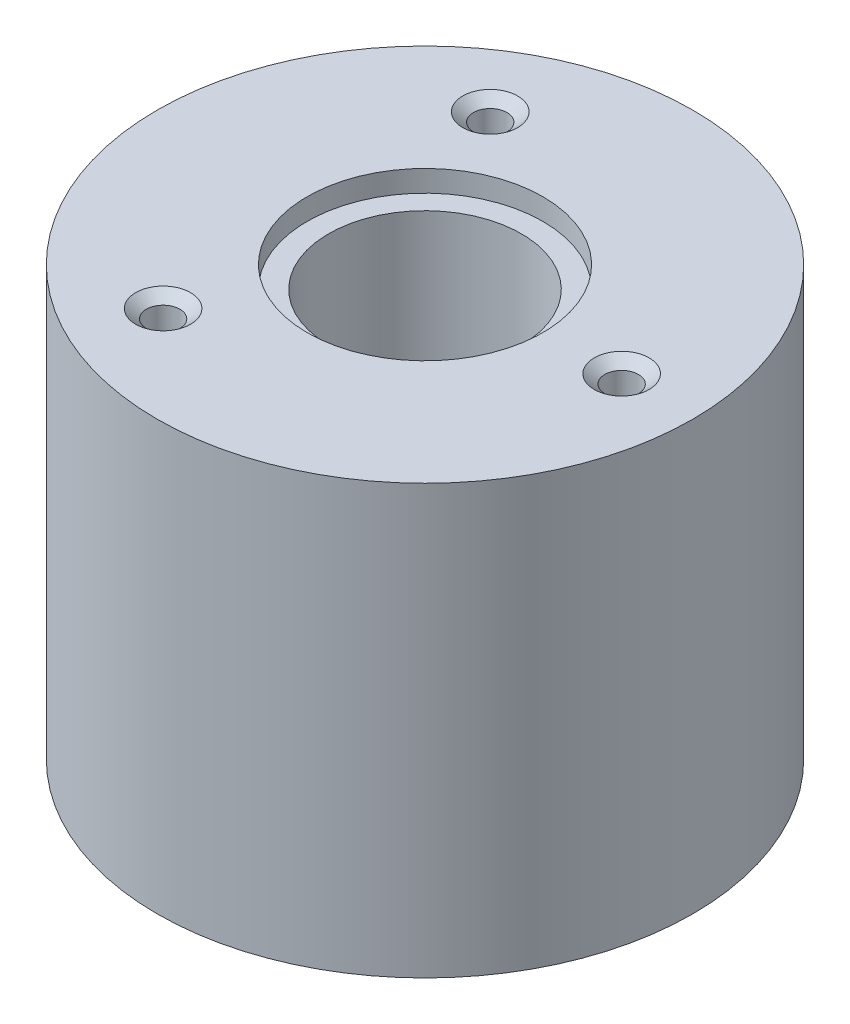
SolidWorks part; units mm, degrees
material "Copper"
ref_plane "Front Plane" through (0, 0, 0) normal (0, 0, 1) x (1, 0, 0)
ref_plane "Top Plane" through (0, 0, 0) normal (0, 1, 0) x (1, 0, 0)
ref_plane "Right Plane" through (0, 0, 0) normal (1, 0, 0) x (0, 0, -1)
sketch "Sketch1" plane through (0, 0, 0) normal (0, 1, 0) x (1, 0, 0)
  circle A0 centre (0, 0) radius 15.875
  dimension "D1" = 31.75
extrude "Boss-Extrude1" add sketch "Sketch1" along normal blind 25.4
sketch "Sketch2" plane through (0, 25.4, 0) normal (0, 1, 0) x (1, 0, 0)
  circle A0 centre (0, 0) radius 5.715
  dimension "D1" = 11.43
extrude "Cut-Extrude1" cut sketch "Sketch2" against normal through all contours A0
sketch "Sketch3" plane through (0, 25.4, 0) normal (0, 1, 0) x (1, 0, 0)
  circle A0 centre (0, 0) radius 6.985
  dimension "D1" = 13.97
extrude "Cut-Extrude2" cut sketch "Sketch3" against normal blind 1.27
hole_wizard "1/4 (0.25) Diameter Hole2" positions "Sketch9" profile "Sketch10" hole size "1/4" standard "ANSI Inch"
sketch "Sketch9" plane through (0, 0, 0) normal (0, -1, 0) x (-1, 0, 0)
  point P0 (-8.9174, -6.4367)
sketch "Sketch10" plane through (8.9174, 0, 6.4367) normal (1, 0, 0) x (0, 0, -1)
  line L0 (0, 0) -> (0, 20.9577)
  line L1 (0, 20.9577) -> (3.175, 19.05)
  line L2 (3.175, 19.05) -> (3.175, 0)
  line L5 (3.175, 0) -> (0, 0)
  line L10 (0, 20.9577) -> (-3.175, 19.05) construction
  line L11 (0, -6.35) -> (0, 107.95) construction
  dimension "Hole Dia." = 6.35
  dimension "Hole Depth" = 19.05
  dimension "Drill Angle" = 118
pattern_circular "CirPattern3" count 2 every 180 about axis through (0, 0, 0) along (0, 1, 0) of "1/4 (0.25) Diameter Hole2"
sketch "Sketch11" plane through (0, 25.4, 0) normal (0, 1, 0) x (1, 0, 0)
  line L0 (0, 0) -> (-5.9142, 9.781)
  line L1 (0, 0) -> (9.5462, 5.6883)
  dimension "D1" = 11.43
  dimension "D2" = 11.1125
hole_wizard "5/64 (0.07813) Diameter Hole1" positions "Sketch12" profile "Sketch13" hole size "5/64" standard "ANSI Inch"
sketch "Sketch12" plane through (0, 25.4, 0) normal (0, 1, 0) x (1, 0, 0)
  point P0 (-5.9142, 9.781)
sketch "Sketch13" plane through (-5.9142, 25.4, -9.781) normal (1, 0, 0) x (0, 0, 1)
  line L0 (0, 0) -> (0, 10.7562)
  line L1 (0, 10.7562) -> (0.9923, 10.16)
  line L2 (0.9923, 10.16) -> (0.9923, 0.5328)
  line L3 (0.9923, 0.5328) -> (1.6273, 0)
  line L5 (1.6273, 0) -> (0, 0)
  line L6 (-0.9923, 0.5328) -> (-1.6273, 0) construction
  line L10 (0, 10.7562) -> (-0.9923, 10.16) construction
  line L11 (0, -6.35) -> (0, 107.95) construction
  dimension "Hole Dia." = 1.9845
  dimension "Hole Depth" = 10.16
  dimension "Near C'Sink Dia." = 3.2545
  dimension "Near C'Sink Angle" = 100
  dimension "Drill Angle" = 118
pattern_circular "CirPattern4" count 3 every 120 about axis through (0, 0, 0) along (0, 1, 0) of "5/64 (0.07813) Diameter Hole1"
sketch "Sketch14" plane through (0, 0, 0) normal (0, -1, 0) x (1, 0, 0)
  line L0 (0, 0) -> (-3.214, -10.6376)
  dimension "D1" = 11.1125
hole_wizard "1/16 (0.0625) Diameter Hole1" positions "Sketch15" profile "Sketch16" hole size "1/16" standard "ANSI Inch"
sketch "Sketch15" plane through (0, 0, 0) normal (0, -1, 0) x (-1, 0, 0)
  point P0 (3.214, 10.6376)
sketch "Sketch16" plane through (-3.214, 0, -10.6376) normal (1, 0, 0) x (0, 0, -1)
  line L0 (0, 0) -> (0, 13.1769)
  line L1 (0, 13.1769) -> (0.7937, 12.7)
  line L2 (0.7937, 12.7) -> (0.7937, 0.5328)
  line L3 (0.7937, 0.5328) -> (1.4287, 0)
  line L5 (1.4287, 0) -> (0, 0)
  line L6 (-0.7937, 0.5328) -> (-1.4287, 0) construction
  line L10 (0, 13.1769) -> (-0.7938, 12.7) construction
  line L11 (0, -6.35) -> (0, 107.95) construction
  dimension "Hole Dia." = 1.5875
  dimension "Hole Depth" = 12.7
  dimension "Near C'Sink Dia." = 2.8575
  dimension "Near C'Sink Angle" = 100
  dimension "Drill Angle" = 118
pattern_circular "CirPattern5" count 2 every 180 about axis through (0, 0, 0) along (0, 1, 0) of "1/16 (0.0625) Diameter Hole1"
